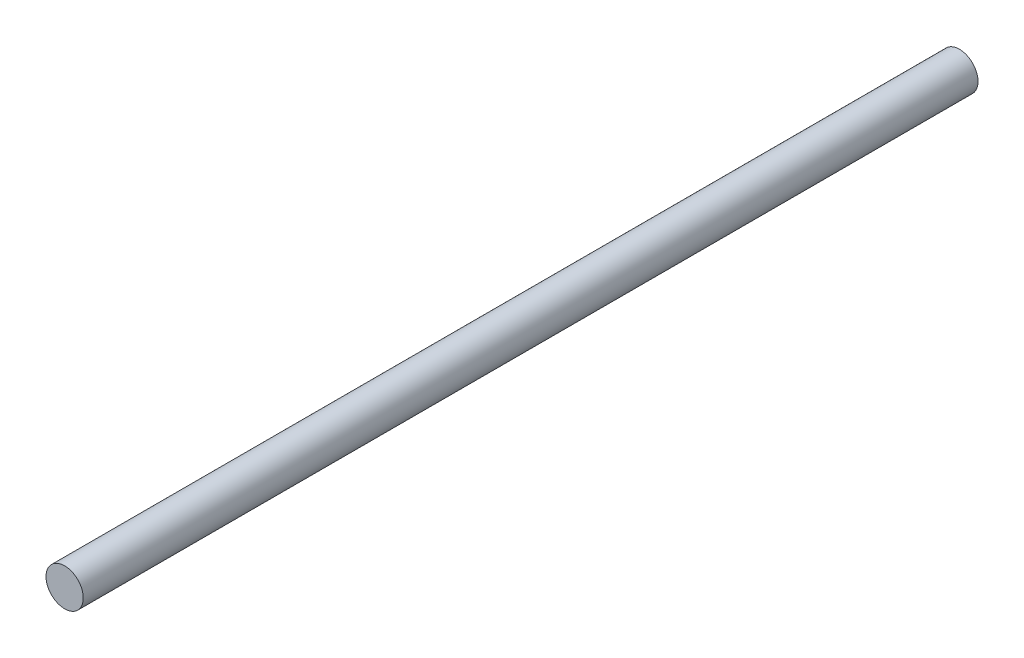
SolidWorks part; units mm, degrees
ref_plane "Front Plane" through (0, 0, 0) normal (0, 0, 1) x (1, 0, 0)
ref_plane "Top Plane" through (0, 0, 0) normal (0, 1, 0) x (1, 0, 0)
ref_plane "Right Plane" through (0, 0, 0) normal (1, 0, 0) x (0, 0, -1)
sketch "Sketch1" plane through (0, 0, 0) normal (0, 0, 1) x (1, 0, 0)
  circle A0 centre (0, 0) radius 3.175
  dimension ".25" = 6.35
extrude "Boss-Extrude1" add sketch "Sketch1" along normal blind 152.4
